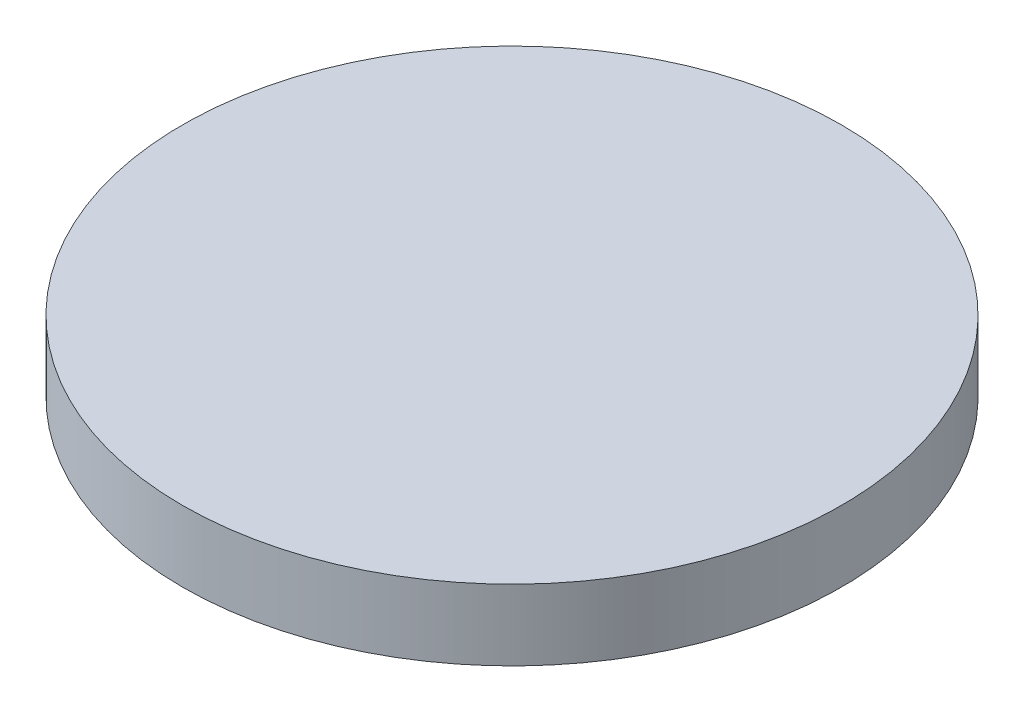
SolidWorks part; units mm, degrees
ref_plane "Front Plane" through (0, 0, 0) normal (0, 0, 1) x (1, 0, 0)
ref_plane "Top Plane" through (0, 0, 0) normal (0, 1, 0) x (1, 0, 0)
ref_plane "Right Plane" through (0, 0, 0) normal (1, 0, 0) x (0, 0, -1)
sketch "Sketch1" plane through (0, 0, 0) normal (0, 1, 0) x (1, 0, 0)
  circle A0 centre (0, 0) radius 18.62
  dimension "D1" = 37.24
extrude "Boss-Extrude1" add sketch "Sketch1" along normal blind 4
